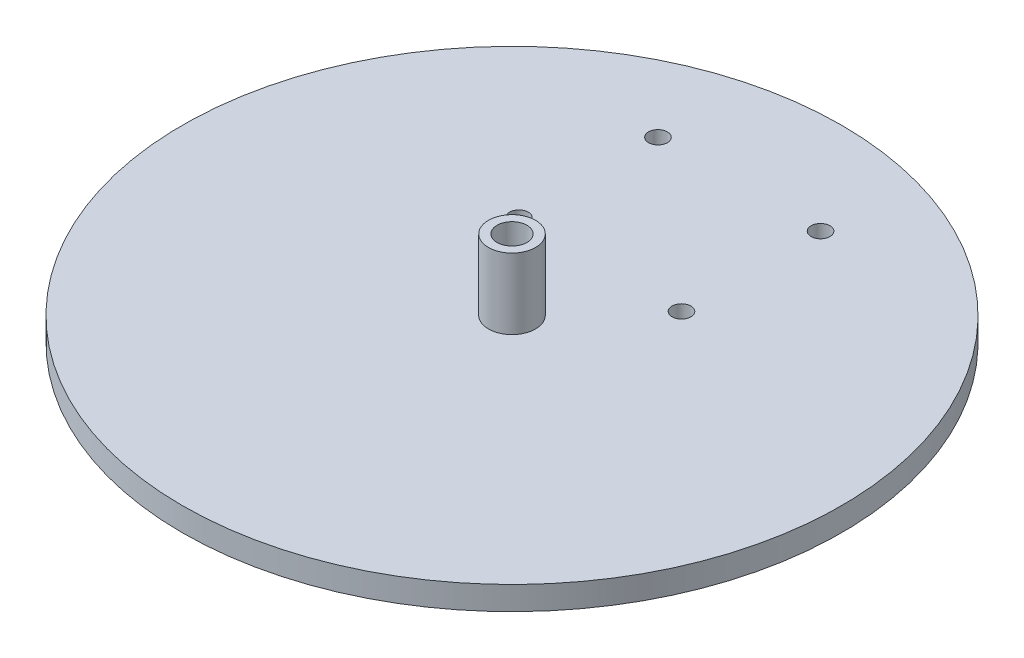
SolidWorks part; units mm, degrees
ref_plane "Front Plane" through (0, 0, 0) normal (0, 0, 1) x (1, 0, 0)
ref_plane "Top Plane" through (0, 0, 0) normal (0, 1, 0) x (1, 0, 0)
ref_plane "Right Plane" through (0, 0, 0) normal (1, 0, 0) x (0, 0, -1)
sketch "Sketch1" plane through (0, 0, 0) normal (0, 1, 0) x (1, 0, 0)
  circle A0 centre (0, 0) radius 3.175
  circle A1 centre (0, 0) radius 70
extrude "Boss-Extrude2" add sketch "Sketch1" along normal blind 5
sketch "Sketch2" plane through (0, 5, 0) normal (0, 1, 0) x (1, 0, 0)
  circle A0 centre (0, 0) radius 5
  circle A1 centre (0, 0) radius 3.175
extrude "Boss-Extrude4" add sketch "Sketch2" along normal blind 15
sketch "Sketch3" plane through (0, 5, 0) normal (0, 1, 0) x (1, 0, 0)
  line L0 (0, 70) -> (0, 46.5)
  line L1 (0, 0) -> (0, 20.5)
  line L2 (70, 0) -> (-70, 0)
  line L3 (0, 20.5) -> (0, -33.5)
  line L8 (0, 46.5) -> (-15.5, 46.5)
  line L9 (-15.5, 46.5) -> (-15.5, 20.5)
  line L10 (-15.5, 20.5) -> (15.5, 20.5)
  line L11 (15.5, 20.5) -> (15.5, 46.5)
  line L12 (15.5, 46.5) -> (0, 46.5)
  line L15 (-15.5, 46.5) -> (-15.5, 44.5)
  line L17 (0, 20.5) -> (0, -70)
  circle A0 centre (0, 0) radius 70 construction
  circle A1 centre (-17.2678, 48.2678) radius 2
  circle A2 centre (17.2678, 48.2678) radius 2
  circle A3 centre (17.2678, 18.7322) radius 2
  circle A4 centre (-17.2678, 18.7322) radius 2
extrude "Cut-Extrude1" cut sketch "Sketch3" against normal blind 10 contours A1 | A2 | A4 | A3
